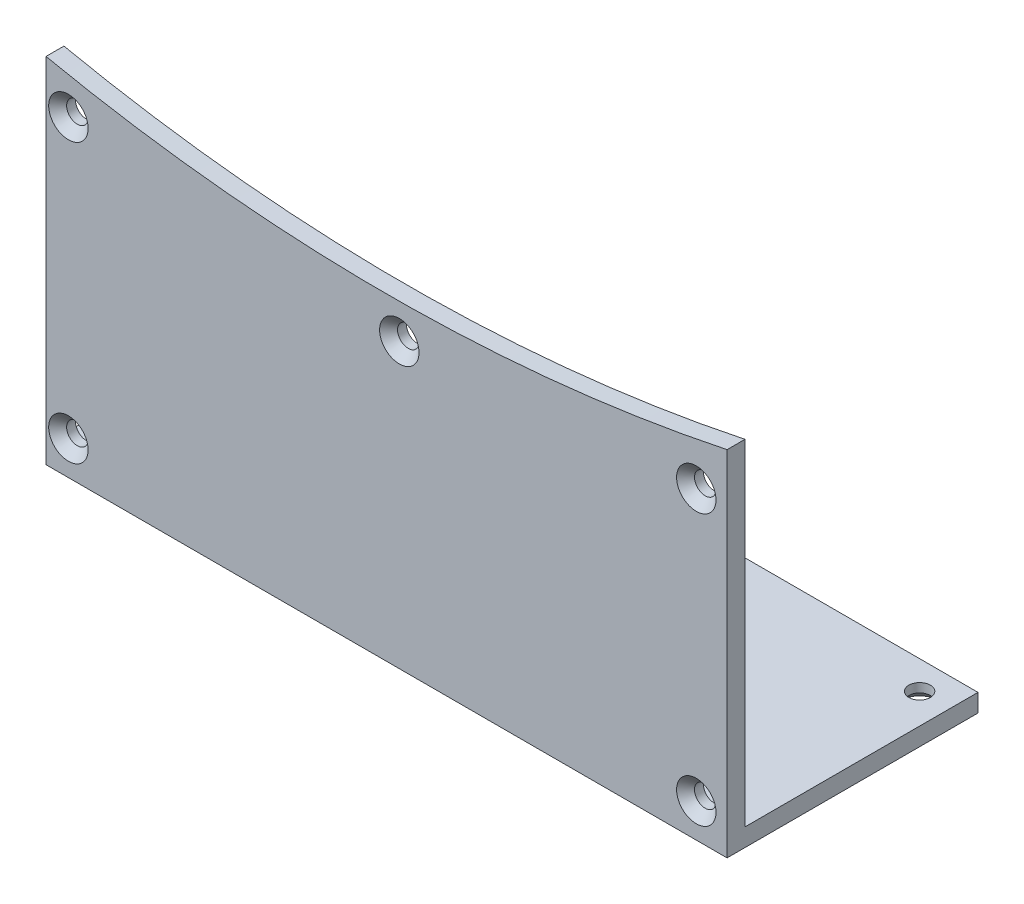
SolidWorks part; units mm, degrees
ref_plane "Plano frontal" through (0, 0, 0) normal (0, 0, 1) x (1, 0, 0)
ref_plane "Plano superior" through (0, 0, 0) normal (0, 1, 0) x (1, 0, 0)
ref_plane "Plano direito" through (0, 0, 0) normal (1, 0, 0) x (0, 0, -1)
sketch "Sketch1" plane through (0, 0, 0) normal (0, 0, 1) x (1, 0, 0)
  line L0 (38, -220) -> (38, -180.5443) construction
  line L1 (-38, -180.5443) -> (-38, -220) construction
  line L2 (38, -220) -> (38, -180.5443)
  line L3 (-38, -180.5443) -> (-38, -220)
  line L4 (-38, -220) -> (38, -220)
  arc A0 (-38, -180.5443) -> (38, -180.5443) centre (0, 0) ccw construction
  arc A1 (-38, -180.5443) -> (38, -180.5443) centre (0, 0) ccw
extrude "Boss-Extrude1" add sketch "Sketch1" against normal blind 2
sketch "Sketch2" plane through (0, 0, -2) normal (0, 0, -1) x (-1, 0, 0)
  line L0 (-38, -220) -> (-38, -180.5443) construction
  line L1 (38, -220) -> (-38, -220)
  line L2 (38, -220) -> (38, -218)
  line L3 (38, -218) -> (-38, -218)
  line L4 (-38, -220) -> (-38, -218)
  line L5 (38, -220) -> (-38, -218) construction
  line L6 (38, -218) -> (-38, -220) construction
  point P4 (0, -219)
  dimension "D1" = 2
extrude "Boss-Extrude2" add sketch "Sketch2" along normal up to surface (26 mm away)
hole_wizard "CSK for M2 Countersunk Flat Head Screw1" positions "Sketch6" profile "Sketch7" countersink size "M2" standard "ISO" end condition through all
sketch "Sketch6" plane through (0, 0, 0) normal (0, 0, 1) x (1, 0, 0)
  line L0 (-38, -180.5443) -> (-38, -220) construction
  arc A0 (-33, -186.6045) -> (33, -186.6045) centre (0, 0) ccw construction
  point P0 (-35.5, -216.2176)
  point P2 (-35.5, -185.1485)
  point P4 (1.4251, -188.3495)
  point P6 (34.5655, -186.0272)
  point P8 (34.5655, -216.2176)
  dimension "D1" = 2.5
  dimension "D2" = 2.5
  dimension "D3" = 188.3549
sketch "Sketch7" plane through (-35.5, -216.2176, 0) normal (1, 0, 0) x (0, -1, 0)
  line L0 (0, 0) -> (0, 28)
  line L1 (0, 28) -> (1.2, 28)
  line L2 (1.2, 28) -> (1.2, 1)
  line L3 (1.2, 1) -> (2.2, 0)
  line L5 (2.2, 0) -> (0, 0)
  line L6 (-1.2, 1) -> (-2.2, 0) construction
  line L11 (0, -6.35) -> (0, 107.95) construction
  dimension "Thru Hole Dia." = 2.4
  dimension "Thru Hole Depth" = 28
  dimension "Near C'Sink Dia." = 4.4
  dimension "Near C'Sink Angle" = 90
hole_wizard "CSK for M2 Countersunk Flat Head Screw2" positions "Sketch8" profile "Sketch9" countersink size "M2" standard "ISO" end condition through all
sketch "Sketch8" plane through (0, -220, 0) normal (0, -1, 0) x (-1, 0, 0)
  point P0 (-34.644, 24.8415)
  point P2 (0, 25.6881)
  point P4 (32.9666, 23.5051)
sketch "Sketch9" plane through (34.644, -220, -24.8415) normal (1, 0, 0) x (0, 0, -1)
  line L0 (0, 0) -> (0, 39.4557)
  line L1 (0, 39.4557) -> (1.2, 39.4557)
  line L2 (1.2, 39.4557) -> (1.2, 1)
  line L3 (1.2, 1) -> (2.2, 0)
  line L5 (2.2, 0) -> (0, 0)
  line L6 (-1.2, 1) -> (-2.2, 0) construction
  line L11 (0, -6.35) -> (0, 107.95) construction
  dimension "Thru Hole Dia." = 2.4
  dimension "Thru Hole Depth" = 39.4557
  dimension "Near C'Sink Dia." = 4.4
  dimension "Near C'Sink Angle" = 90
